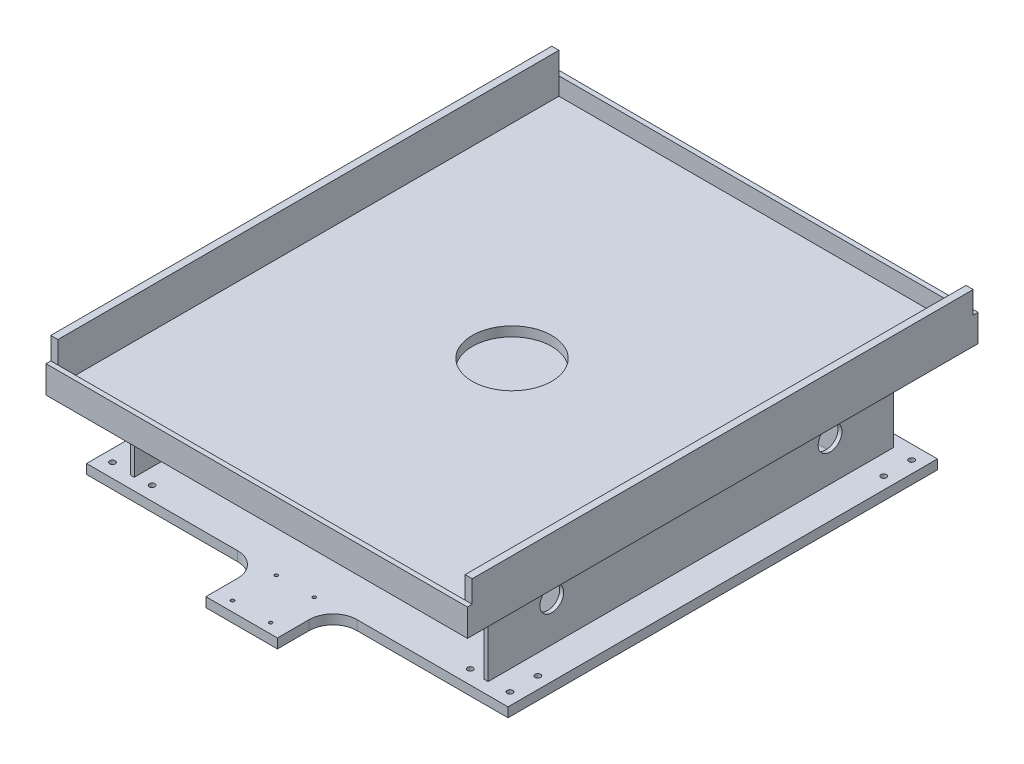
SolidWorks part; units mm, degrees
ref_plane "Front" through (0, 0, 0) normal (0, 0, 1) x (1, 0, 0)
ref_plane "Top" through (0, 0, 0) normal (0, 1, 0) x (1, 0, 0)
ref_plane "Right" through (0, 0, 0) normal (1, 0, 0) x (0, 0, -1)
sketch "Sketch1" plane through (0, 0, 0) normal (0, 1, 0) x (1, 0, 0)
  line L0 (0, -40.4133) -> (0, 736.8791) construction
  line L1 (-265, 680) -> (265, 680)
  line L2 (-265, 680) -> (-265, 0)
  line L3 (-265, 0) -> (265, 0)
  line L4 (265, 680) -> (265, 0)
  dimension "D1" = 530
  dimension "D2" = 680
extrude "Boss-Extrude1" add sketch "Sketch1" along normal blind 12
sketch "Sketch2" plane through (0, 0, 0) normal (1, 0, 0) x (0, 0, -1)
  line L0 (0, 12) -> (680, 12) construction
  line L1 (85, 112) -> (595, 112)
  line L2 (85, 112) -> (85, 12)
  line L3 (85, 12) -> (595, 12)
  line L4 (595, 112) -> (595, 12)
  line L5 (0, 12) -> (0, 0) construction
  line L6 (0, 0) -> (680, 0) construction
  dimension "D1" = 85
  dimension "D2" = 112
  dimension "D3" = 510
extrude "Boss-Extrude2" add sketch "Sketch2" along normal blind 5 from offset 220
sketch "Sketch3" plane through (0, 0, 0) normal (1, 0, 0) x (0, 0, -1)
  line L4 (85, 112) -> (85, 12)
  line L5 (85, 12) -> (595, 12)
  line L6 (595, 12) -> (595, 112)
  line L7 (595, 112) -> (85, 112)
  line L8 (85, 112) -> (85, 12)
  line L9 (85, 12) -> (595, 12)
  line L10 (595, 12) -> (595, 112)
  line L11 (595, 112) -> (85, 112)
  dimension "D1" = 0
extrude "Boss-Extrude3" add sketch "Sketch3" against normal blind 5 from offset 220 offset against normal yes
sketch "Sketch4" plane through (-220, 0, 0) normal (1, 0, 0) x (0, 0, -1)
  line L0 (595, 112) -> (85, 112) construction
  line L1 (135, 112) -> (185, 112)
  line L2 (135, 112) -> (135, 12)
  line L3 (135, 12) -> (185, 12)
  line L4 (185, 112) -> (185, 12)
  line L5 (85, 12) -> (595, 12) construction
  line L6 (0, 12) -> (0, 0) construction
  line L7 (595, 112) -> (85, 112) construction
  line L8 (495, 112) -> (545, 112)
  line L9 (495, 112) -> (495, 12)
  line L10 (495, 12) -> (545, 12)
  line L11 (545, 112) -> (545, 12)
  dimension "D1" = 50
  dimension "D2" = 135
  dimension "D3" = 310
  dimension "D4" = 50
extrude "Extrude-Thin1" add sketch "Sketch4" along normal up to surface (440 mm away) separate body thin
sketch "Sketch5" plane through (0, 112, 0) normal (0, 1, 0) x (1, 0, 0)
  line L0 (0, -23.4441) -> (0, 713.3002) construction
  line L1 (-265, 0) -> (265, 0) construction
  line L2 (-265, 661) -> (265, 661)
  line L3 (-265, 661) -> (-265, 19)
  line L4 (-265, 19) -> (265, 19)
  line L5 (265, 661) -> (265, 19)
  line L6 (265, 0) -> (265, 680) construction
  dimension "D2" = 19
  dimension "D3" = 642
extrude "Boss-Extrude4" add sketch "Sketch5" along normal blind 62 separate body
shell "Shell1" thickness 9
fillet "Fillet1" radius 6 4 edges at (0, 109, -182) (0, 109, -138) (0, 15, -182) (0, 15, -138)
fillet "Fillet2" radius 9 4 edges at (0, 112, -185) (0, 12, -185) (0, 12, -135) (0, 112, -135)
fillet "Fillet3" radius 6 4 edges at (0, 15, -498) (0, 109, -498) (0, 109, -542) (0, 15, -542)
fillet "Fillet4" radius 9 4 edges at (0, 12, -545) (0, 12, -495) (0, 112, -495) (0, 112, -545)
combine bodies "Combine1" operation type add bodies to combine 106 105 104 103
sketch "Sketch6" plane through (0, 174, 0) normal (0, 1, 0) x (1, 0, 0)
  line L0 (265, 19) -> (265, 661) construction
  line L1 (-265, 19) -> (265, 19)
  line L2 (-265, 19) -> (-265, 25)
  line L3 (-265, 25) -> (265, 25)
  line L4 (265, 19) -> (265, 25)
  line L5 (-256, 25) -> (256, 25) construction
  line L6 (256, 655) -> (-256, 655) construction
  line L7 (-265, 661) -> (265, 661)
  line L8 (-265, 661) -> (-265, 655)
  line L9 (-265, 655) -> (265, 655)
  line L10 (265, 661) -> (265, 655)
extrude "Cut-Extrude1" cut sketch "Sketch6" against normal blind 27.8
sketch "Sketch7" plane through (0, 12, 0) normal (0, 1, 0) x (1, 0, 0)
  line L0 (0, -45.0663) -> (0, 722.1042) construction
  line L1 (-265, 0) -> (-45, 0)
  line L2 (-265, 0) -> (-265, 70)
  line L3 (-265, 70) -> (-45, 70)
  line L4 (-45, 0) -> (-45, 70)
  line L5 (265, 0) -> (45, 0)
  line L6 (265, 0) -> (265, 70)
  line L7 (265, 70) -> (45, 70)
  line L8 (45, 0) -> (45, 70)
  line L9 (265, 680) -> (45, 680)
  line L10 (265, 680) -> (265, 610)
  line L11 (265, 610) -> (45, 610)
  line L12 (45, 680) -> (45, 610)
  line L13 (-265, 680) -> (-45, 680)
  line L14 (-265, 680) -> (-265, 610)
  line L15 (-265, 610) -> (-45, 610)
  line L16 (-45, 680) -> (-45, 610)
  dimension "D1" = 90
  dimension "D2" = 70
  dimension "D3" = 540
extrude "Cut-Extrude2" cut sketch "Sketch7" against normal through all
sketch "Sketch8" plane through (0, 124, 0) normal (0, 1, 0) x (1, 0, 0)
  line L0 (-45, 0) -> (45, 0) construction
  circle A0 centre (0, 340) radius 50
  dimension "D1" = 100
  dimension "D2" = 340
extrude "Cut-Extrude3" cut sketch "Sketch8" against normal through all
sketch "Sketch9" plane through (225, 0, 0) normal (1, 0, 0) x (0, 0, -1)
  line L0 (70, 0) -> (0, 0) construction
  line L1 (0, 0) -> (0, 12) construction
  circle A0 centre (165, 62) radius 15
  circle A1 centre (515, 62) radius 15
  dimension "D1" = 62
  dimension "D3" = 350
  dimension "D4" = 30
  dimension "D2" = 165
extrude "Cut-Extrude4" cut sketch "Sketch9" against normal through all
hole_wizard "M5x0.8 Tapped Hole1" positions "Sketch11" profile "Sketch10" tap size "M5x0.8" standard "JIS"
sketch "Sketch11" plane through (0, 12, 0) normal (0, 1, 0) x (-1, 0, 0)
  line L0 (0, 55.4334) -> (0, -711.737) construction
  line L2 (45, 0) -> (-45, 0) construction
  point P0 (-24, -12.5)
  point P1 (24, -12.5)
  point P3 (-24, -67.5)
  point P5 (24, -67.5)
  dimension "D1" = 48
  dimension "D2" = 12.5
  dimension "D3" = 55
sketch "Sketch10" plane through (24, 12, -12.5) normal (1, 0, 0) x (0, 0, 1)
  line L0 (0, 0) -> (0, 12)
  line L1 (0, 12) -> (2.1, 12)
  line L2 (2.1, 12) -> (2.1, 0)
  line L5 (2.1, 0) -> (0, 0)
  line L11 (0, -6.35) -> (0, 107.95) construction
  dimension "Thru Tap Drill Dia." = 4.2
  dimension "Thru Tap Drill Depth" = 12
cosmetic thread "Hole Thread1" parameters "D2"=5
cosmetic thread "Hole Thread2" parameters "D2"=5
cosmetic thread "Hole Thread3" parameters "D2"=5
cosmetic thread "Hole Thread4" parameters "D2"=5
pattern_linear "LPattern1" count 2 spacing 600 along (0, 0, -1) of "M5x0.8 Tapped Hole1"
hole_wizard "Ø7.0 (7) Diameter Hole1" positions "Sketch13" profile "Sketch12" hole size "Ø7.0" standard "JIS"
sketch "Sketch13" plane through (0, 12, 0) normal (0, 1, 0) x (-1, 0, 0)
  line L0 (0, 25.1136) -> (0, -702.0281) construction
  line L2 (45, 0) -> (-45, 0) construction
  point P1 (-200, -122.5)
  point P3 (-200, -87.5)
  point P5 (-250, -122.5)
  point P7 (-250, -87.5)
  dimension "D1" = 400
  dimension "D2" = 50
  dimension "D3" = 35
  dimension "D4" = 87.5
sketch "Sketch12" plane through (200, 12, -122.5) normal (1, 0, 0) x (0, 0, 1)
  line L0 (0, 0) -> (0, 12)
  line L1 (0, 12) -> (3.5, 12)
  line L2 (3.5, 12) -> (3.5, 0)
  line L5 (3.5, 0) -> (0, 0)
  line L11 (0, -6.35) -> (0, 107.95) construction
  dimension "Thru Hole Dia." = 7
  dimension "Thru Hole Depth" = 12
mirror "Mirror1" about plane through (0, 0, 0) normal (1, 0, 0) of "Ø7.0 (7) Diameter Hole1"
pattern_linear "LPattern2" count 2 spacing 470 along (0, 0, -1) of "Mirror1", "Ø7.0 (7) Diameter Hole1"
fillet "Fillet5" radius 30 4 edges at (45, 6, -610) (-45, 6, -610) (-45, 6, -70) (45, 6, -70)
